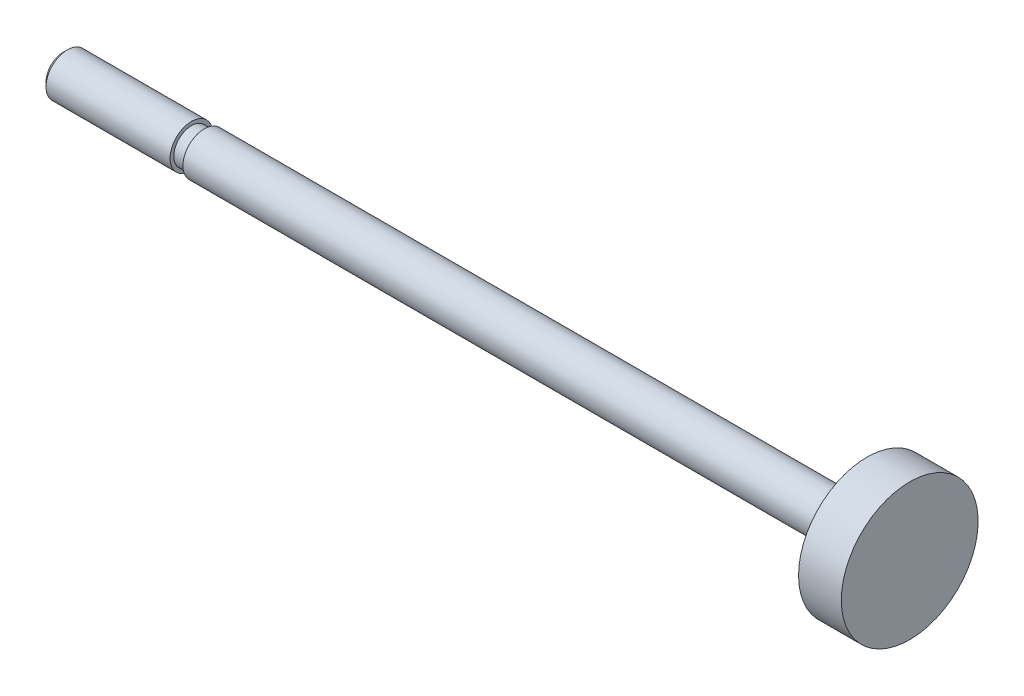
SolidWorks part; units mm, degrees
ref_plane "Front Plane" through (0, 0, 0) normal (0, 0, 1) x (1, 0, 0)
ref_plane "Top Plane" through (0, 0, 0) normal (0, 1, 0) x (1, 0, 0)
ref_plane "Right Plane" through (0, 0, 0) normal (1, 0, 0) x (0, 0, -1)
ref_plane "Plane1" through (0, 0, 0) normal (0, 0, 1) x (1, 0, 0)
sketch "Sketch1" plane through (0, 0, 0) normal (0, 0, 1) x (1, 0, 0)
  line L0 (0, 0) -> (0, 2.0095)
  line L1 (0, 2.0095) -> (0.4905, 2.5)
  line L2 (0.4905, 2.5) -> (15, 2.5)
  line L3 (15, 2.5) -> (15, 2.067)
  line L4 (15, 2.067) -> (16.5, 2.067)
  line L5 (16.5, 2.067) -> (16.5, 2.5)
  line L6 (16.5, 2.5) -> (94, 2.5)
  line L7 (94, 2.5) -> (94, 8)
  line L8 (94, 8) -> (99, 8)
  line L9 (99, 8) -> (99, 0)
  line L10 (99, 0) -> (0, 0)
  line L11 (99, 0) -> (0, 0) construction
revolve "Revolve1" add sketch "Sketch1" angle 360 about L11
cosmetic thread "Cosmetic Thread1"
